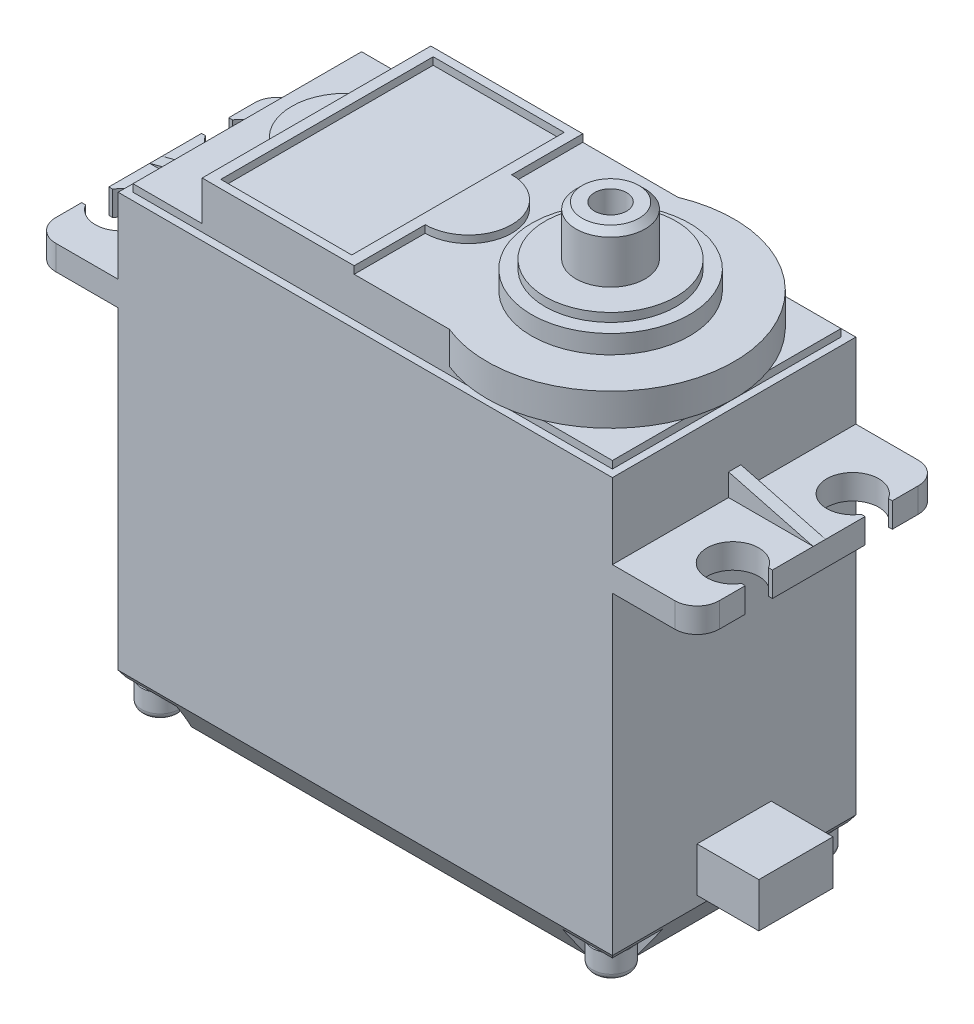
SolidWorks part; units mm, degrees
ref_plane "Front Plane" through (0, 0, 0) normal (0, 0, 1) x (1, 0, 0)
ref_plane "Top Plane" through (0, 0, 0) normal (0, 1, 0) x (1, 0, 0)
ref_plane "Right Plane" through (0, 0, 0) normal (1, 0, 0) x (0, 0, -1)
sketch "Sketch1" plane through (0, 0, 0) normal (0, 0, 1) x (1, 0, 0)
  line L1 (20, -18.25) -> (-20, -18.25)
  line L2 (20, -18.25) -> (20, 18.25)
  line L3 (20, 18.25) -> (-20, 18.25)
  line L4 (-20, -18.25) -> (-20, 18.25)
  line L5 (20, -18.25) -> (-20, 18.25) construction
  line L6 (20, 18.25) -> (-20, -18.25) construction
  point P0 (0, 0)
  dimension "D1" = 40
  dimension "D2" = 36.5
extrude "Boss-Extrude1" add sketch "Sketch1" along normal blind 19.7 contours L4 L3 L2 L1
chamfer "Chamfer1" distance 2 distance2 3 4 edges at (0, -18.25, 0) (-20, -18.25, 9.85) (0, -18.25, 19.7) (20, -18.25, 9.85)
sketch "Sketch2" plane through (0, -18.25, 0) normal (0, -1, 0) x (1, 0, 0)
  line L0 (20, 19.7) -> (20, 0) construction
  line L1 (-20, 19.7) -> (20, 19.7) construction
  line L2 (20, 0) -> (-20, 0) construction
  line L3 (-20, 0) -> (-20, 19.7) construction
  line L6 (20, 15.3) -> (20, 19.7)
  line L7 (20, 19.7) -> (15.6, 19.7)
  line L10 (20, 4.4) -> (20, 0)
  line L11 (20, 0) -> (15.6, 0)
  line L13 (-15.6, 0) -> (-20, 0)
  line L16 (-20, 0) -> (-20, 4.4)
  line L18 (-20, 15.3) -> (-20, 19.7)
  line L19 (-20, 19.7) -> (-15.6, 19.7)
  arc A0 (20, 15.3) -> (15.6, 19.7) centre (20, 19.7) cw
  arc A1 (20, 4.4) -> (15.6, 0) centre (20, 0) ccw
  arc A2 (-20, 4.4) -> (-15.6, 0) centre (-20, 0) cw
  arc A3 (-15.6, 19.7) -> (-20, 15.3) centre (-20, 19.7) cw
  dimension "D1" = 4.4
extrude "Cut-Extrude1" cut sketch "Sketch2" against normal blind 2.5
sketch "Sketch4" plane through (0, -15.75, 0) normal (0, -1, 0) x (1, 0, 0)
  circle A0 centre (-18.295, 18.0012) radius 1.5
  circle A1 centre (18.205, 18.0012) radius 1.5
  circle A2 centre (18.205, 1.7512) radius 1.5
  circle A3 centre (-18.295, 1.7512) radius 1.5
  dimension "D1" = 3
  dimension "D2" = 2
  dimension "D3" = 2
extrude "Boss-Extrude2" add sketch "Sketch4" along normal blind 2 contours A1 | A2 | A3 | A0
fillet "Fillet1" radius 0.5 1 edges at (-16.795, -17.75, 18.0012)
fillet "Fillet3" radius 0.5 1 edges at (-16.795, -17.75, 1.7512)
fillet "Fillet4" radius 0.5 1 edges at (19.705, -17.75, 1.7512)
fillet "Fillet5" radius 0.5 1 edges at (19.705, -17.75, 18.0012)
ref_plane "Plane1" through (0, 10.15, 0) normal (0, -1, 0) x (-1, 0, 0)
sketch "Sketch5" plane through (0, 10.15, 0) normal (0, -1, 0) x (-1, 0, 0)
  line L0 (20, -19.7) -> (-20, 0)
  line L1 (20, -19.7) -> (-20, -19.7)
  line L2 (20, -19.7) -> (20, 0)
  line L3 (20, 0) -> (-20, 0)
  line L4 (-20, -19.7) -> (-20, 0)
  line L5 (-20, -19.7) -> (20, 0)
  line L7 (26.85, 0) -> (-26.85, 0)
  line L8 (26.85, 0) -> (26.85, -19.7)
  line L9 (26.85, -19.7) -> (-26.85, -19.7)
  line L10 (-26.85, 0) -> (-26.85, -19.7)
  line L11 (26.85, 0) -> (-26.85, -19.7) construction
  line L12 (26.85, -19.7) -> (-26.85, 0) construction
  point P6 (0, -9.85)
  dimension "D1" = 53.7
extrude "Boss-Extrude3" add sketch "Sketch5" against normal blind 2 contours L10 L9 L8 L7
sketch "Sketch6" plane through (0, 10.15, 0) normal (0, -1, 0) x (1, 0, 0)
  line L0 (26.85, 0) -> (26.85, 19.7) construction
  line L1 (26.85, 3.9) -> (26.5389, 3.9)
  line L2 (26.85, 0) -> (26.85, 19.7) construction
  line L3 (26.85, 6.1) -> (26.5389, 6.1)
  line L4 (26.85, 6.1) -> (26.85, 3.9)
  line L5 (0, 19.7) -> (0, 0) construction
  line L7 (-20, 19.7) -> (20, 19.7) construction
  line L8 (26.85, 9.85) -> (-26.85, 9.85) construction
  line L9 (-26.85, 0) -> (-26.85, 19.7) construction
  line L10 (26.85, 13.6) -> (26.85, 15.8)
  line L11 (26.85, 13.6) -> (26.5389, 13.6)
  line L12 (-26.85, 15.8) -> (-26.5389, 15.8)
  line L13 (26.85, 15.8) -> (26.5389, 15.8)
  line L14 (-26.85, 13.6) -> (-26.5389, 13.6)
  line L15 (-26.85, 13.6) -> (-26.85, 15.8)
  line L16 (-26.85, 6.1) -> (-26.85, 3.9)
  line L17 (-26.85, 6.1) -> (-26.5389, 6.1)
  line L18 (-26.85, 3.9) -> (-26.5389, 3.9)
  line L22 (20, 19.7) -> (26.85, 19.7) construction
  line L23 (20, 0) -> (20, 19.7) construction
  arc A0 (26.5389, 15.8) -> (26.5389, 13.6) centre (24.75, 14.7) ccw
  arc A1 (26.5389, 3.9) -> (26.5389, 6.1) centre (24.75, 5) cw
  arc A2 (-26.5389, 3.9) -> (-26.5389, 6.1) centre (-24.75, 5) ccw
  arc A3 (-26.5389, 15.8) -> (-26.5389, 13.6) centre (-24.75, 14.7) cw
  dimension "D1" = 5
  dimension "D2" = 4.75
  dimension "D3" = 0
extrude "Cut-Extrude2" cut sketch "Sketch6" against normal blind 2
fillet "Fillet9" radius 1.8 4 edges at (26.85, 11.15, 0) (-26.85, 11.15, 0) (-26.85, 11.15, 19.7) (26.85, 11.15, 19.7)
ref_plane "Plane2" through (0, 0, 10.3) normal (0, 0, 1) x (1, 0, 0)
sketch "Sketch7" plane through (0, 0, 10.3) normal (0, 0, 1) x (1, 0, 0)
  line L0 (-26.85, 12.15) -> (-20, 13.95)
  line L2 (-26.85, 12.15) -> (-20, 12.15)
  line L3 (-20, 12.15) -> (-20, 13.95)
  line L4 (0, -1000) -> (0, 49000) construction
  line L5 (20, 12.15) -> (20, 13.95)
  line L6 (26.85, 12.15) -> (20, 12.15)
  line L7 (26.85, 12.15) -> (20, 13.95)
  dimension "D1" = 1.8
extrude "Boss-Extrude4" add sketch "Sketch7" against normal blind 1
sketch "Sketch8" plane through (0, 18.25, 0) normal (0, 1, 0) x (1, 0, 0)
  line L0 (20, -19.7) -> (-20, 0) construction
  line L1 (20, 0) -> (-20, -19.7) construction
  line L2 (20, -19.7) -> (-20, -19.7) construction
  line L3 (-19.4, -0.6) -> (19.4, -0.6)
  line L4 (-19.4, -0.6) -> (-19.4, -19.1)
  line L5 (-19.4, -19.1) -> (19.4, -19.1)
  line L6 (19.4, -0.6) -> (19.4, -19.1)
  line L7 (-19.4, -0.6) -> (19.4, -19.1) construction
  line L8 (-19.4, -19.1) -> (19.4, -0.6) construction
  line L9 (20, -10.3) -> (20, -19.7) construction
  point P8 (0, -9.85)
  point P9 (0, -9.85)
  dimension "D1" = 0.6
  dimension "D2" = 0.6
extrude "Boss-Extrude5" add sketch "Sketch8" along normal blind 0.6 contours L6 L5 L4 L3
sketch "Sketch9" plane through (0, 18.85, 0) normal (0, 1, 0) x (1, 0, 0)
  line L0 (20, -19.7) -> (20, 0) construction
  line L1 (-13.7997, -6.1622) -> (-13.7997, -0.6)
  line L2 (6.2003, -19.1) -> (-13.7997, -19.1)
  line L3 (6.2003, -0.6) -> (-13.7997, -0.6)
  line L4 (-13.7997, -19.1) -> (-13.7997, -13.5378)
  line L5 (-19.4, -19.1) -> (19.4, -19.1) construction
  arc A0 (6.2003, -19.1) -> (6.2003, -0.6) centre (10, -9.85) ccw
  arc A1 (-13.7997, -6.1622) -> (-13.7997, -13.5378) centre (-11.3997, -9.85) ccw
  point P2 (20, -9.85)
  dimension "D1" = 10
  dimension "D2" = 20
  dimension "D4" = 8.8
  dimension "D3" = 20
  dimension "D5" = 2.4
extrude "Boss-Extrude6" add sketch "Sketch9" along normal blind 2.6
sketch "Sketch10" plane through (0, 21.45, 0) normal (0, 1, 0) x (1, 0, 0)
  line L0 (-13.7997, -19.1) -> (-13.7997, -0.6)
  line L1 (-13.7997, -19.1) -> (-1.4997, -19.1)
  line L2 (-13.7997, -0.6) -> (-1.4997, -0.6)
  line L3 (-1.4997, -19.1) -> (-1.4997, -13.35)
  line L4 (-13.7997, -9.85) -> (-1.4997, -9.85) construction
  line L5 (-12.9497, -1.2547) -> (-2.3497, -1.2547)
  line L6 (-12.9497, -1.2547) -> (-12.9497, -18.4453)
  line L7 (-12.9497, -18.4453) -> (-2.3497, -18.4453)
  line L8 (-2.3497, -1.2547) -> (-2.3497, -18.4453)
  line L9 (-12.9497, -1.2547) -> (-2.3497, -18.4453) construction
  line L10 (-12.9497, -18.4453) -> (-2.3497, -1.2547) construction
  line L11 (-7.6497, -19.1) -> (-7.6497, -0.6) construction
  line L12 (-1.4997, -6.35) -> (-1.4997, -0.6)
  arc A0 (-1.4997, -13.35) -> (-1.4997, -6.35) centre (-1.4997, -9.85) ccw
  point P0 (-7.6497, -9.85)
  dimension "D3" = 3.5
  dimension "D1" = 12.3
  dimension "D2" = 10.6
extrude "Boss-Extrude7" add sketch "Sketch10" along normal blind 0.6
sketch "Sketch11" plane through (0, 21.45, 0) normal (0, 1, 0) x (1, 0, 0)
  circle A0 centre (10, -9.85) radius 6.4
  dimension "D1" = 12.8
extrude "Boss-Extrude8" add sketch "Sketch11" along normal blind 1.5
sketch "Sketch12" plane through (0, 22.95, 0) normal (0, 1, 0) x (1, 0, 0)
  circle A0 centre (10, -9.85) radius 5.3
extrude "Boss-Extrude9" add sketch "Sketch12" along normal blind 0.7
sketch "Sketch13" plane through (0, 23.65, 0) normal (0, 1, 0) x (1, 0, 0)
  circle A0 centre (10, -9.85) radius 2.8
  circle A1 centre (10, -9.85) radius 1.3
  dimension "D1" = 5.6
extrude "Boss-Extrude10" add sketch "Sketch13" along normal blind 4 contours A0 A1
chamfer "Chamfer2" distance 0.5 angle 45 1 edges at (10, 27.65, 12.65)
sketch "Sketch14" plane through (0, 23.65, 0) normal (0, 1, 0) x (1, 0, 0)
  line L0 (10, -9.85) -> (10, -12.15)
  line L1 (10, -9.85) -> (9.428, -12.0777)
  line L2 (10, -9.85) -> (8.892, -11.8655)
  line L3 (10, -9.85) -> (8.4255, -11.5266)
  line L4 (10, -9.85) -> (8.058, -11.0824)
  line L5 (10, -9.85) -> (7.8126, -10.5607)
  line L6 (10, -9.85) -> (7.7045, -9.9944)
  line L7 (10, -9.85) -> (7.7407, -9.419)
  line L8 (10, -9.85) -> (7.9189, -8.8707)
  line L9 (10, -9.85) -> (8.2278, -8.3839)
  line L10 (10, -9.85) -> (8.6481, -7.9893)
  line L11 (10, -9.85) -> (9.1533, -7.7115)
  line L12 (10, -9.85) -> (9.7117, -7.5681)
  line L13 (10, -9.85) -> (10.2883, -7.5681)
  line L14 (10, -9.85) -> (10.8467, -7.7115)
  line L15 (10, -9.85) -> (11.3519, -7.9893)
  line L16 (10, -9.85) -> (11.7722, -8.3839)
  line L17 (10, -9.85) -> (12.0811, -8.8707)
  line L18 (10, -9.85) -> (12.2593, -9.419)
  line L19 (10, -9.85) -> (12.2955, -9.9944)
  line L20 (10, -9.85) -> (12.1874, -10.5607)
  line L21 (10, -9.85) -> (11.942, -11.0824)
  line L22 (10, -9.85) -> (11.5745, -11.5266)
  line L23 (10, -9.85) -> (11.108, -11.8655)
  line L24 (10, -9.85) -> (10.572, -12.0777)
  circle A0 centre (10, -9.85) radius 2.8
  circle A1 centre (10, -9.85) radius 2.3
  point P32 (10, -9.85)
  dimension "D1" = 25
sketch "Sketch15" plane through (0, -17.75, 0) normal (0, -1, 0) x (1, 0, 0)
  line L0 (18.055, 1.6012) -> (18.055, 0.9012)
  line L1 (18.355, 2.6012) -> (18.055, 2.6012)
  line L2 (18.355, 2.6012) -> (18.355, 1.9012)
  line L3 (18.355, 0.9012) -> (18.055, 0.9012)
  line L4 (18.055, 2.6012) -> (18.055, 1.9012)
  line L5 (18.355, 2.6012) -> (18.055, 0.9012) construction
  line L6 (18.355, 0.9012) -> (18.055, 2.6012) construction
  line L7 (17.355, 1.6012) -> (18.055, 1.6012)
  line L8 (17.355, 1.6012) -> (17.355, 1.9012)
  line L9 (17.355, 1.9012) -> (18.055, 1.9012)
  line L10 (19.055, 1.6012) -> (19.055, 1.9012)
  line L11 (17.355, 1.6012) -> (19.055, 1.9012) construction
  line L12 (17.355, 1.9012) -> (19.055, 1.6012) construction
  line L13 (18.355, 1.6012) -> (19.055, 1.6012)
  line L14 (18.355, 1.9012) -> (19.055, 1.9012)
  line L15 (18.355, 1.6012) -> (18.355, 0.9012)
  point P0 (18.205, 1.7512)
  point P6 (18.205, 1.7512)
  dimension "D1" = 0.3
  dimension "D2" = 0.3
  dimension "D3" = 1.7
  dimension "D4" = 1.7
extrude "Cut-Extrude3" cut sketch "Sketch15" against normal blind 1.2
pattern_linear "LPattern1" count 2 spacing 36.5 along (-1, 0, 0) count 2 spacing 16.3 along (0, 0, 1) of "Cut-Extrude3"
sketch "Sketch16" plane through (20, 0, 0) normal (1, 0, 0) x (0, 0, -1)
  line L1 (-6.85, -10.85) -> (-12.85, -10.85)
  line L2 (-6.85, -10.85) -> (-6.85, -14.45)
  line L3 (-6.85, -14.45) -> (-12.85, -14.45)
  line L4 (-12.85, -10.85) -> (-12.85, -14.45)
  line L5 (-6.85, -10.85) -> (-12.85, -14.45) construction
  line L6 (-6.85, -14.45) -> (-12.85, -10.85) construction
  line L11 (-9.85, 18.25) -> (-9.85, -18.25) construction
  line L12 (-0.6, 18.25) -> (-19.1, 18.25) construction
  line L13 (-3.9192, -18.25) -> (-15.7808, -18.25) construction
  point P0 (-9.85, -12.65)
  dimension "D1" = 3.6
  dimension "D2" = 6
  dimension "D3" = 3.8
extrude "Boss-Extrude11" add sketch "Sketch16" along normal blind 5
sketch "Sketch17" plane through (25, 0, 0) normal (1, 0, 0) x (0, 0, -1)
  line L0 (-6.85, -14.45) -> (-6.85, -10.85) construction
  arc A0 (-10.775, -13.0016) -> (-8.925, -13.0016) centre (-9.85, -12.6216) ccw
  arc A1 (-8.925, -13.0016) -> (-8.925, -12.2417) centre (-7.9223, -12.6216) ccw
  arc A2 (-10.775, -12.2417) -> (-10.775, -13.0016) centre (-11.7, -12.6216) ccw
  arc A3 (-8.925, -12.2417) -> (-10.775, -12.2417) centre (-9.85, -12.6216) ccw
  dimension "D1" = 2
  dimension "D2" = 3
